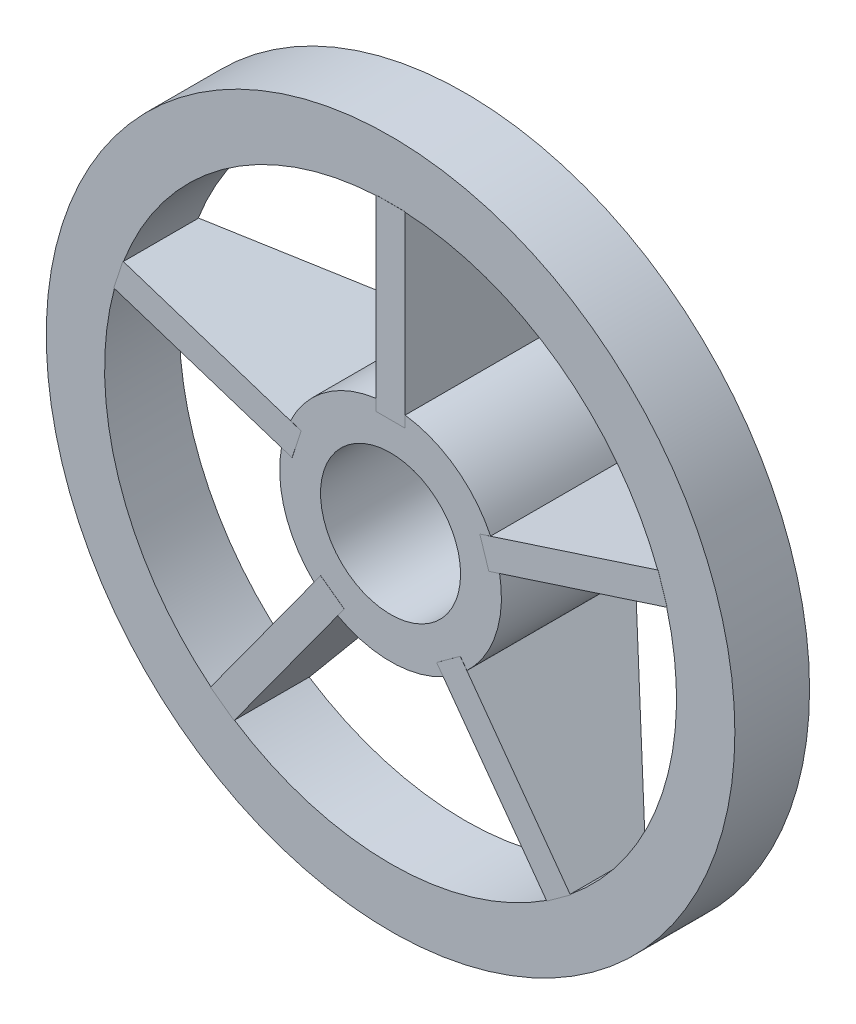
SolidWorks part; units mm, degrees
ref_plane "Front Plane" through (0, 0, 0) normal (0, 0, 1) x (1, 0, 0)
ref_plane "Top Plane" through (0, 0, 0) normal (0, 1, 0) x (1, 0, 0)
ref_plane "Right Plane" through (0, 0, 0) normal (1, 0, 0) x (0, 0, -1)
sketch "Sketch1" plane through (0, 0, 0) normal (0, 0, 1) x (1, 0, 0)
  circle A0 centre (0, 0) radius 7.5
  circle A1 centre (0, 0) radius 11.875
  dimension "D1" = 15
  dimension "D2" = 4.375
extrude "Boss-Extrude1" add sketch "Sketch1" along normal blind 18
sketch "Sketch2" plane through (0, 0, 18) normal (0, 0, 1) x (1, 0, 0)
  circle A1 centre (0, 0) radius 36.875
  circle A2 centre (0, 0) radius 30.625
  circle A3 centre (0, 0) radius 30.625
  dimension "D1" = 18.75
  dimension "D2" = 6.25
extrude "Boss-Extrude2" add sketch "Sketch2" against normal blind 8 separate body
sketch "Sketch3" plane through (0, 0, 0) normal (1, 0, 0) x (0, 0, -1)
  line L0 (-18.0112, 30.6405) -> (-9.9807, 30.6405)
  line L1 (-9.9807, 30.6405) -> (0, 11.8196)
  line L2 (0, 11.8196) -> (-18.0112, 11.8196) construction
  line L3 (-18.0112, 11.8196) -> (-18.0112, 30.6405)
  line L4 (0, 10.5696) -> (-18.0112, 10.5696)
  line L5 (-18.0112, 11.8196) -> (-18.0112, 10.5696)
  line L6 (0, 11.8196) -> (0, 10.5696)
  dimension "D1" = 1.25
extrude "Boss-Extrude3" add sketch "Sketch3" along normal mid plane 3.125
pattern_circular "CirPattern1" count 5 over 360 about axis through (0, 0, 0) along (0, 0, 1) of "Boss-Extrude3"
